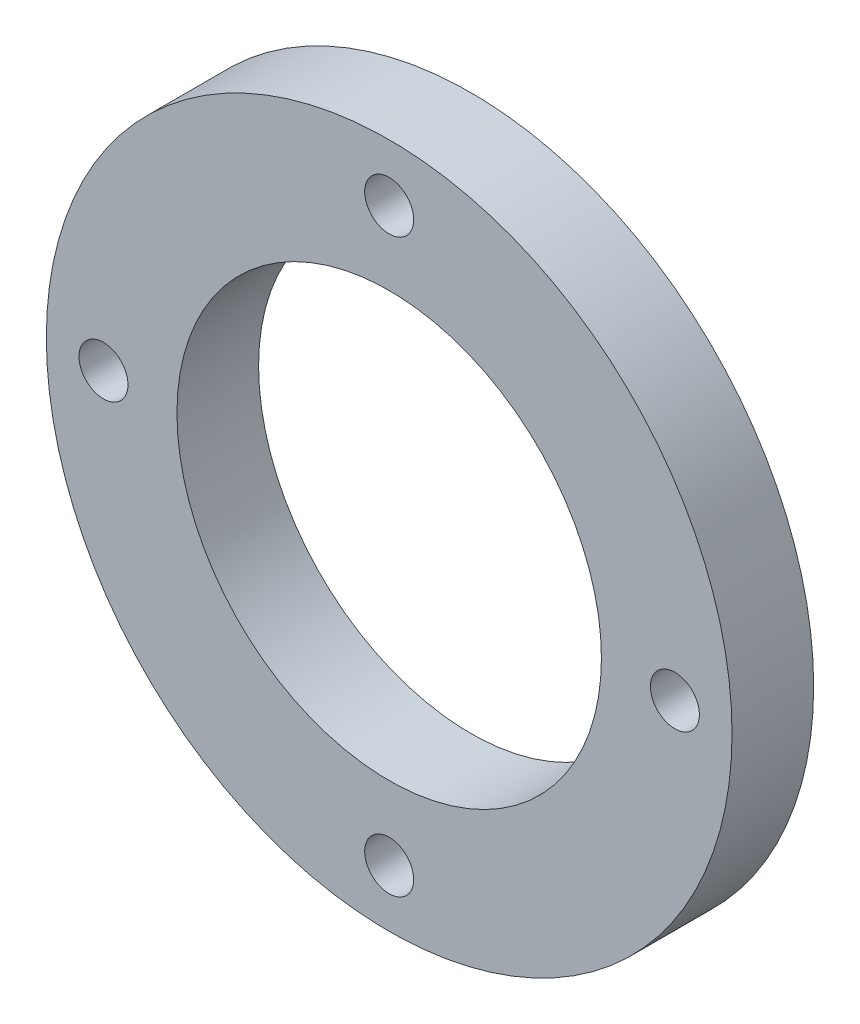
SolidWorks part; units mm, degrees
material "Thornel Mat VMA"
ref_plane "Front Plane" through (0, 0, 0) normal (0, 0, 1) x (1, 0, 0)
ref_plane "Top Plane" through (0, 0, 0) normal (0, 1, 0) x (1, 0, 0)
ref_plane "Right Plane" through (0, 0, 0) normal (1, 0, 0) x (0, 0, -1)
sketch "Sketch1" plane through (0, 0, 0) normal (0, 0, 1) x (1, 0, 0)
  circle A0 centre (49, 5) radius 13 construction
  circle A1 centre (31.5, 5) radius 1.5 construction
  circle A2 centre (49, 22.5) radius 1.5 construction
  circle A3 centre (66.5, 5) radius 1.5 construction
  circle A4 centre (49, -12.5) radius 1.5 construction
  circle A5 centre (49, 5) radius 13
  circle A6 centre (31.5, 5) radius 1.5
  circle A7 centre (49, 22.5) radius 1.5
  circle A8 centre (66.5, 5) radius 1.5
  circle A9 centre (49, -12.5) radius 1.5
  arc A10 (49, -16) -> (49, 26) centre (49, 5) ccw construction
  circle A11 centre (49, 5) radius 21
extrude "Boss-Extrude1" add sketch "Sketch1" along normal blind 5
